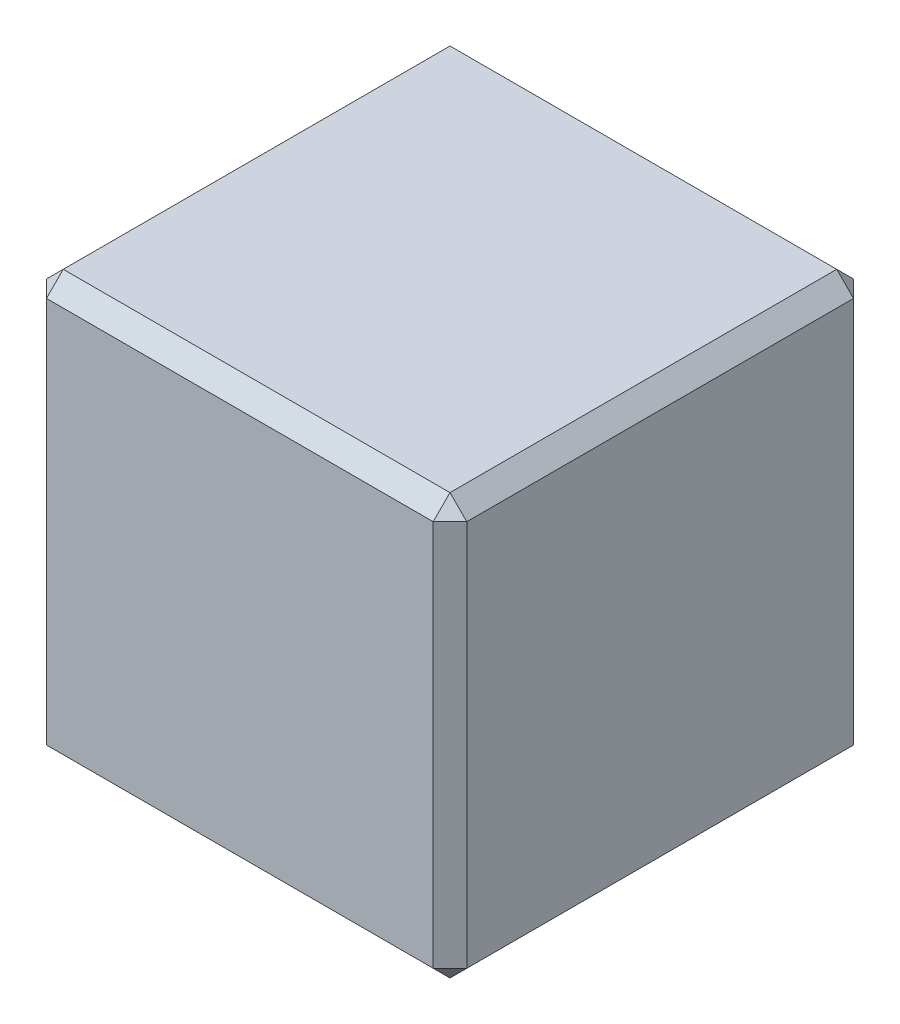
SolidWorks part; units mm, degrees
ref_plane "Plan de face" through (0, 0, 0) normal (0, 0, 1) x (1, 0, 0)
ref_plane "Plan de dessus" through (0, 0, 0) normal (0, 1, 0) x (1, 0, 0)
ref_plane "Plan de droite" through (0, 0, 0) normal (1, 0, 0) x (0, 0, -1)
sketch "Esquisse1" plane through (0, 0, 0) normal (0, 0, 1) x (1, 0, 0)
  line L1 (0, 0) -> (50, 0)
  line L2 (0, 0) -> (0, 50)
  line L3 (0, 50) -> (50, 50)
  line L4 (50, 0) -> (50, 50)
  dimension "D1" = 50
  dimension "D2" = 50
extrude "Boss.-Extru.1" add sketch "Esquisse1" along normal blind 50
chamfer "Chanfrein1" distance 2 angle 45 12 edges at (0, 0, 25) (25, 0, 0) (0, 25, 0) (50, 0, 25) (50, 25, 0) (50, 50, 25) (25, 50, 0) (0, 50, 25) (25, 50, 50) (50, 25, 50) (25, 0, 50) (0, 25, 50)
